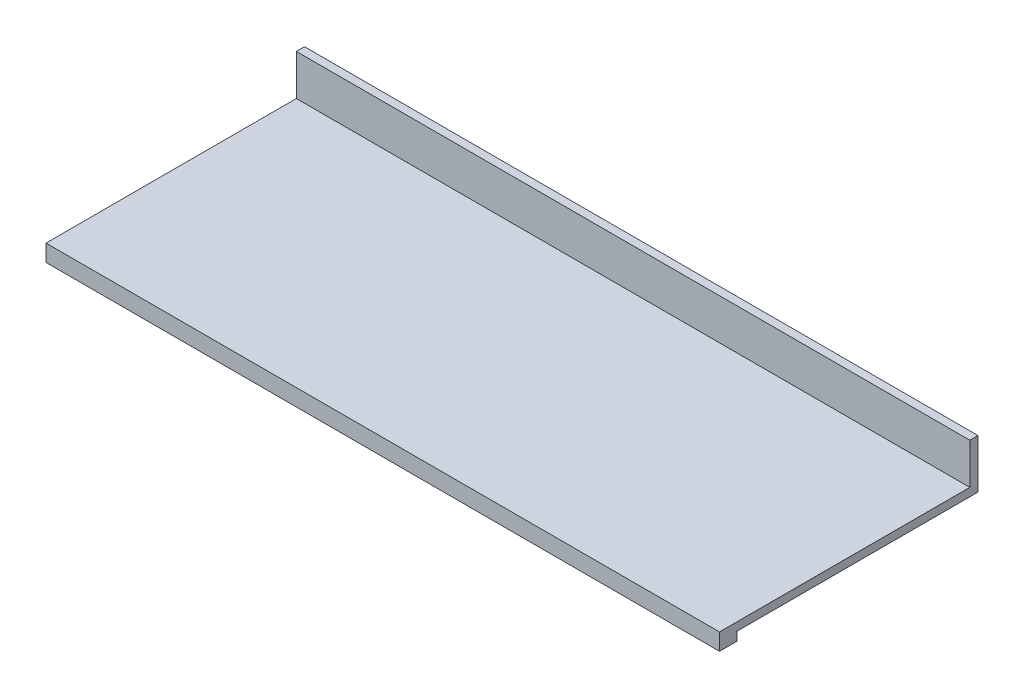
SolidWorks part; units mm, degrees
ref_plane "Front Plane" through (0, 0, 0) normal (0, 0, 1) x (1, 0, 0)
ref_plane "Top Plane" through (0, 0, 0) normal (0, 1, 0) x (1, 0, 0)
ref_plane "Right Plane" through (0, 0, 0) normal (1, 0, 0) x (0, 0, -1)
sketch "Sketch1" plane through (0, 0, 0) normal (0, 1, 0) x (1, 0, 0)
  line L1 (-495, -190) -> (495, -190)
  line L2 (-495, -190) -> (-495, 190)
  line L3 (-495, 190) -> (495, 190)
  line L4 (495, -190) -> (495, 190)
  line L5 (-495, -190) -> (495, 190) construction
  line L6 (-495, 190) -> (495, -190) construction
  point P0 (0, 0)
  dimension "D1" = 990
  dimension "D2" = 380
extrude "Boss-Extrude1" add sketch "Sketch1" along normal blind 12
sketch "Sketch2" plane through (0, 0, 0) normal (0, -1, 0) x (1, 0, 0)
  line L0 (495, 190) -> (495, -190) construction
  line L1 (-495, 190) -> (495, 190)
  line L2 (-495, 190) -> (-495, 164.6)
  line L3 (-495, 164.6) -> (495, 164.6)
  line L4 (495, 190) -> (495, 164.6)
  dimension "D1" = 25.4
extrude "Boss-Extrude2" add sketch "Sketch2" along normal blind 12.7
sketch "Sketch3" plane through (0, 12, 0) normal (0, 1, 0) x (1, 0, 0)
  line L0 (-495, 190) -> (-495, -190) construction
  line L1 (495, 190) -> (-495, 190)
  line L2 (495, 190) -> (495, 178)
  line L3 (495, 178) -> (-495, 178)
  line L4 (-495, 190) -> (-495, 178)
  dimension "D1" = 12
extrude "Boss-Extrude3" add sketch "Sketch3" along normal blind 60
